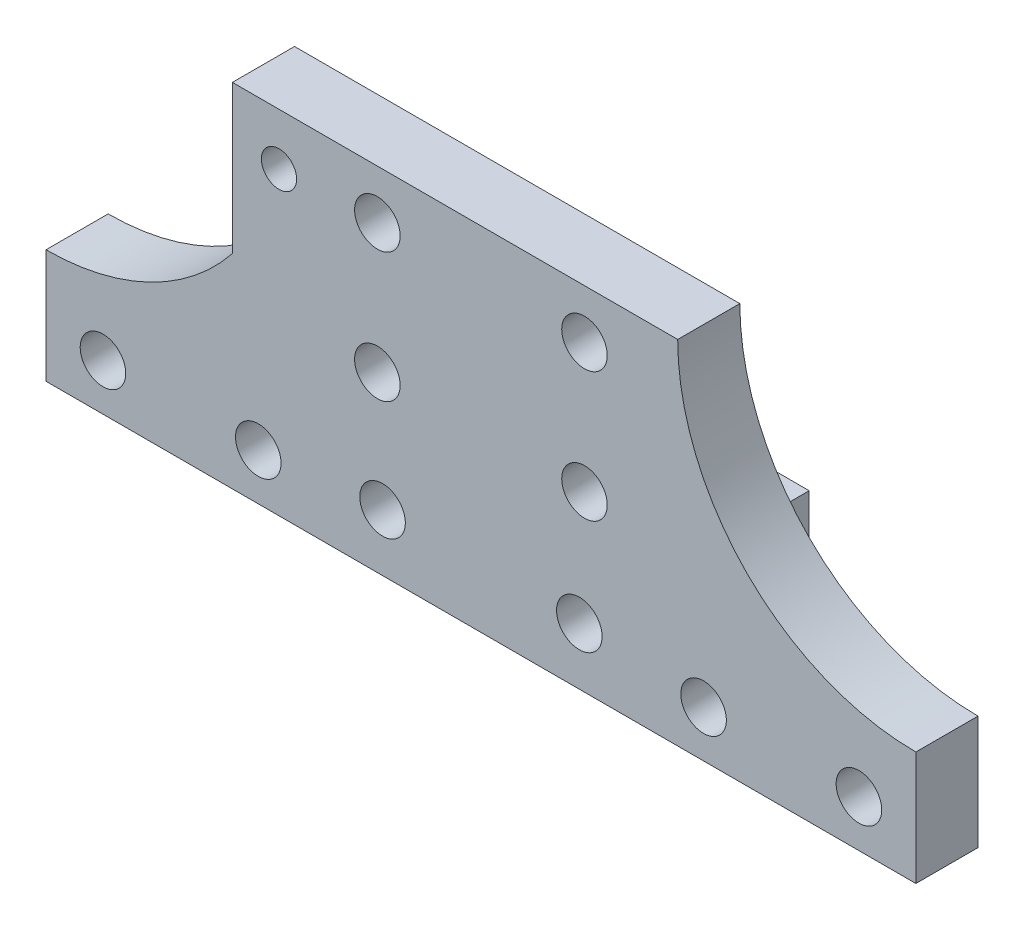
SolidWorks part; units mm, degrees
ref_plane "Front Plane" through (0, 0, 0) normal (0, 0, 1) x (1, 0, 0)
ref_plane "Top Plane" through (0, 0, 0) normal (0, 1, 0) x (1, 0, 0)
ref_plane "Right Plane" through (0, 0, 0) normal (1, 0, 0) x (0, 0, -1)
ref_plane "Plane1" through (0, 0, -14.3) normal (0, 0, -1) x (-1, 0, 0)
sketch "Sketch1" plane through (0, 0, -14.3) normal (0, 0, -1) x (-1, 0, 0)
  line L0 (-15.5, 29.5) -> (-15.5, -4.5)
  line L1 (-15.5, -4.5) -> (68.5, -4.5)
  line L2 (68.5, -4.5) -> (68.5, 29.5)
  line L3 (68.5, 29.5) -> (-15.5, 29.5)
extrude "Boss-Extrude1" add sketch "Sketch1" against normal blind 6
sketch "Sketch2" plane through (0, 0, -8.3) normal (0, 0, 1) x (1, 0, 0)
  line L0 (-68.5, 29.5) -> (-68.5, 6.5)
  line L1 (-50.5, 15.1822) -> (-50.5, 29.5)
  line L2 (-50.5, 29.5) -> (-68.5, 29.5)
  arc A0 (-68.5, 6.5) -> (-50.5, 15.1822) centre (-68.5, 29.5) ccw
extrude "Cut-Extrude1" cut sketch "Sketch2" against normal through all
sketch "Sketch3" plane through (0, 0, -14.3) normal (0, 0, -1) x (-1, 0, 0)
  line L0 (11.5, 6.5) -> (41.5, 6.5)
  line L1 (41.5, 6.5) -> (41.5, -4.5)
  line L2 (41.5, -4.5) -> (11.5, -4.5)
  line L3 (11.5, -4.5) -> (11.5, 6.5)
extrude "Boss-Extrude2" add sketch "Sketch3" along normal blind 10.7
hole_wizard "Hole1" positions "Sketch5" profile "Sketch4" legacy
sketch "Sketch5" plane through (0, 0, -14.3) normal (0, 0, -1) x (-1, 0, 0)
  point P0 (46, 24.5)
sketch "Sketch4" plane through (-46, 24.5, -14.3) normal (1, 0, 0) x (0, 1, 0)
  line L0 (0, 0) -> (0, 6)
  line L1 (0, 6) -> (1.7, 6)
  line L2 (1.7, 6) -> (1.7, 0)
  line L3 (1.7, 0) -> (0, 0)
  line L4 (0, 110) -> (0, -10) construction
  dimension "Diameter" = 3.4
  dimension "Depth" = 6
hole_wizard "Hole2" positions "Sketch7" profile "Sketch6" legacy
sketch "Sketch7" plane through (0, 0, -14.3) normal (0, 0, -1) x (-1, 0, 0)
  point P0 (-15.5, 29.5)
sketch "Sketch6" plane through (15.5, 29.5, -14.3) normal (1, 0, 0) x (0, 1, 0)
  line L0 (0, 0) -> (0, 6)
  line L1 (0, 6) -> (23, 6)
  line L2 (23, 6) -> (23, 0)
  line L3 (23, 0) -> (0, 0)
  line L4 (0, 110) -> (0, -10) construction
  dimension "Diameter" = 46
  dimension "Depth" = 6
hole_wizard "Hole3" positions "Sketch9" profile "Sketch8" legacy
sketch "Sketch9" plane through (0, 0, -14.3) normal (0, 0, -1) x (-1, 0, 0)
  point P0 (16.5, 12.25)
sketch "Sketch8" plane through (-16.5, 12.25, -14.3) normal (1, 0, 0) x (0, 1, 0)
  line L0 (0, 0) -> (0, 6)
  line L1 (0, 6) -> (2.2, 6)
  line L2 (2.2, 6) -> (2.2, 0)
  line L3 (2.2, 0) -> (0, 0)
  line L4 (0, 110) -> (0, -10) construction
  dimension "Diameter" = 4.4
  dimension "Depth" = 6
hole_wizard "Hole4" positions "Sketch11" profile "Sketch10" legacy
sketch "Sketch11" plane through (0, 0, -14.3) normal (0, 0, -1) x (-1, 0, 0)
  point P0 (36.5, 12.25)
sketch "Sketch10" plane through (-36.5, 12.25, -14.3) normal (1, 0, 0) x (0, 1, 0)
  line L0 (0, 0) -> (0, 6)
  line L1 (0, 6) -> (2.2, 6)
  line L2 (2.2, 6) -> (2.2, 0)
  line L3 (2.2, 0) -> (0, 0)
  line L4 (0, 110) -> (0, -10) construction
  dimension "Diameter" = 4.4
  dimension "Depth" = 6
hole_wizard "Hole5" positions "Sketch13" profile "Sketch12" legacy
sketch "Sketch13" plane through (0, 0, -14.3) normal (0, 0, -1) x (-1, 0, 0)
  point P0 (36.5, 24.75)
sketch "Sketch12" plane through (-36.5, 24.75, -14.3) normal (1, 0, 0) x (0, 1, 0)
  line L0 (0, 0) -> (0, 6)
  line L1 (0, 6) -> (2.2, 6)
  line L2 (2.2, 6) -> (2.2, 0)
  line L3 (2.2, 0) -> (0, 0)
  line L4 (0, 110) -> (0, -10) construction
  dimension "Diameter" = 4.4
  dimension "Depth" = 6
hole_wizard "Hole6" positions "Sketch15" profile "Sketch14" legacy
sketch "Sketch15" plane through (0, 0, -14.3) normal (0, 0, -1) x (-1, 0, 0)
  point P0 (16.5, 24.75)
sketch "Sketch14" plane through (-16.5, 24.75, -14.3) normal (1, 0, 0) x (0, 1, 0)
  line L0 (0, 0) -> (0, 6)
  line L1 (0, 6) -> (2.2, 6)
  line L2 (2.2, 6) -> (2.2, 0)
  line L3 (2.2, 0) -> (0, 0)
  line L4 (0, 110) -> (0, -10) construction
  dimension "Diameter" = 4.4
  dimension "Depth" = 6
hole_wizard "Hole7" positions "Sketch17" profile "Sketch16" legacy
sketch "Sketch17" plane through (0, 0, -25) normal (0, 0, -1) x (-1, 0, 0)
  point P0 (36, 1)
sketch "Sketch16" plane through (-36, 1, -25) normal (1, 0, 0) x (0, 1, 0)
  line L0 (0, 0) -> (0, 16.7)
  line L1 (0, 16.7) -> (2.2, 16.7)
  line L2 (2.2, 16.7) -> (2.2, 0)
  line L3 (2.2, 0) -> (0, 0)
  line L4 (0, 110) -> (0, -10) construction
  dimension "Diameter" = 4.4
  dimension "Depth" = 16.7
hole_wizard "Hole8" positions "Sketch19" profile "Sketch18" legacy
sketch "Sketch19" plane through (0, 0, -14.3) normal (0, 0, -1) x (-1, 0, 0)
  point P0 (48, 0)
sketch "Sketch18" plane through (-48, 0, -14.3) normal (1, 0, 0) x (0, 1, 0)
  line L0 (0, 0) -> (0, 6)
  line L1 (0, 6) -> (2.2, 6)
  line L2 (2.2, 6) -> (2.2, 0)
  line L3 (2.2, 0) -> (0, 0)
  line L4 (0, 110) -> (0, -10) construction
  dimension "Diameter" = 4.4
  dimension "Depth" = 6
hole_wizard "Hole9" positions "Sketch21" profile "Sketch20" legacy
sketch "Sketch21" plane through (0, 0, -14.3) normal (0, 0, -1) x (-1, 0, 0)
  point P0 (63, 0)
sketch "Sketch20" plane through (-63, 0, -14.3) normal (1, 0, 0) x (0, 1, 0)
  line L0 (0, 0) -> (0, 6)
  line L1 (0, 6) -> (2.2, 6)
  line L2 (2.2, 6) -> (2.2, 0)
  line L3 (2.2, 0) -> (0, 0)
  line L4 (0, 110) -> (0, -10) construction
  dimension "Diameter" = 4.4
  dimension "Depth" = 6
hole_wizard "Hole10" positions "Sketch23" profile "Sketch22" legacy
sketch "Sketch23" plane through (0, 0, -8.3) normal (0, 0, 1) x (1, 0, 0)
  point P0 (-17, 1)
sketch "Sketch22" plane through (-17, 1, -8.3) normal (1, 0, 0) x (0, -1, 0)
  line L0 (0, 0) -> (0, 16.7)
  line L1 (0, 16.7) -> (2.2, 16.7)
  line L2 (2.2, 16.7) -> (2.2, 0)
  line L3 (2.2, 0) -> (0, 0)
  line L4 (0, 110) -> (0, -10) construction
  dimension "Diameter" = 4.4
  dimension "Depth" = 16.7
hole_wizard "Hole11" positions "Sketch25" profile "Sketch24" legacy
sketch "Sketch25" plane through (0, 0, -14.3) normal (0, 0, -1) x (-1, 0, 0)
  point P0 (5, 0)
sketch "Sketch24" plane through (-5, 0, -14.3) normal (1, 0, 0) x (0, 1, 0)
  line L0 (0, 0) -> (0, 6)
  line L1 (0, 6) -> (2.2, 6)
  line L2 (2.2, 6) -> (2.2, 0)
  line L3 (2.2, 0) -> (0, 0)
  line L4 (0, 110) -> (0, -10) construction
  dimension "Diameter" = 4.4
  dimension "Depth" = 6
hole_wizard "Hole12" positions "Sketch27" profile "Sketch26" legacy
sketch "Sketch27" plane through (0, 0, -14.3) normal (0, 0, -1) x (-1, 0, 0)
  point P0 (-10, 0)
sketch "Sketch26" plane through (10, 0, -14.3) normal (1, 0, 0) x (0, 1, 0)
  line L0 (0, 0) -> (0, 6)
  line L1 (0, 6) -> (2.2, 6)
  line L2 (2.2, 6) -> (2.2, 0)
  line L3 (2.2, 0) -> (0, 0)
  line L4 (0, 110) -> (0, -10) construction
  dimension "Diameter" = 4.4
  dimension "Depth" = 6
hole_wizard "Hole13" positions "Sketch29" profile "Sketch28" legacy
sketch "Sketch29" plane through (0, -4.5, 0) normal (0, -1, 0) x (1, 0, 0)
  point P0 (-26.5, -25)
sketch "Sketch28" plane through (-26.5, -4.5, -25) normal (1, 0, 0) x (0, 0, -1)
  line L0 (0, 0) -> (0, 34)
  line L1 (0, 34) -> (4, 34)
  line L2 (4, 34) -> (4, 0)
  line L3 (4, 0) -> (0, 0)
  line L4 (0, 110) -> (0, -10) construction
  dimension "Diameter" = 8
  dimension "Depth" = 34
ref_plane "Plane2" through (-26.5, 0, 0) normal (-1, 0, 0) x (0, -1, 0)
sketch "Sketch30" plane through (-26.5, 0, 0) normal (-1, 0, 0) x (0, -1, 0)
  line L0 (-29.5, -14.3) -> (-6.5, -21)
rib "Rib1" sketch "Sketch30" sketch "Sketch30" thickness 5 extrusion direction parallel to sketch draft on no parameters "D1"=5
